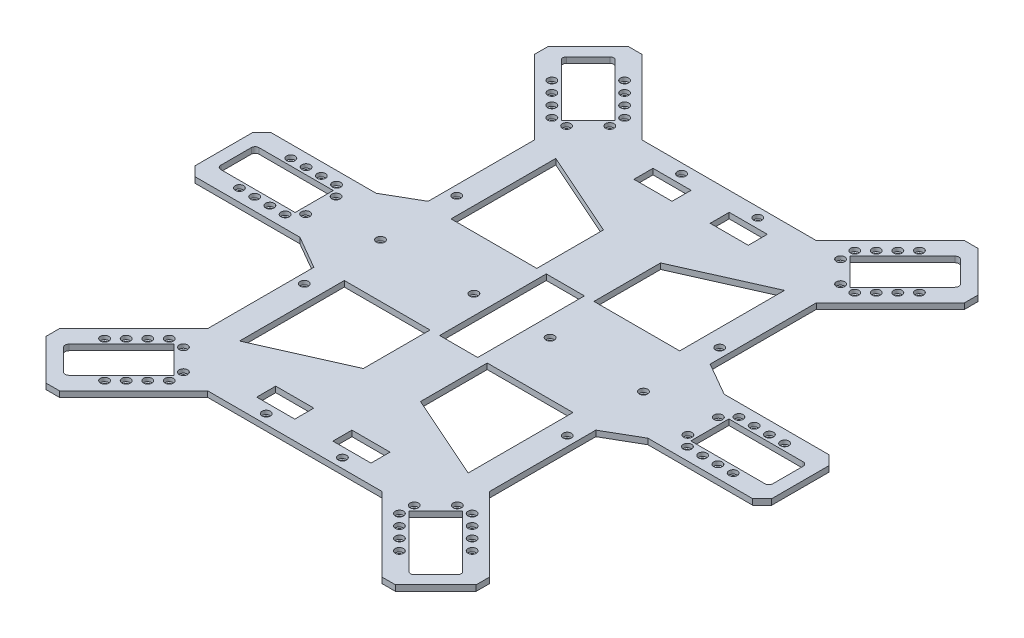
SolidWorks part; units mm, degrees
ref_plane "Front" through (0, 0, 0) normal (0, 0, 1) x (1, 0, 0)
ref_plane "Top" through (0, 0, 0) normal (0, 1, 0) x (1, 0, 0)
ref_plane "Right" through (0, 0, 0) normal (1, 0, 0) x (0, 0, -1)
sketch "草图1" plane through (0, 0, 0) normal (0, 1, 0) x (1, 0, 0)
  line L0 (-45.7157, 114) -> (45.7157, 114)
  line L1 (-74, 0) -> (74, 0) construction
  line L2 (74, -30) -> (91.3205, -20)
  line L3 (91.3205, -20) -> (146.3205, -20)
  line L4 (151.3205, -15) -> (151.3205, 15)
  line L5 (-60, 100) -> (60, -100) construction
  line L6 (-60, -100) -> (60, 100) construction
  line L7 (74, -30) -> (74, -85.7157)
  line L8 (-45.7157, -114) -> (45.7157, -114)
  line L9 (-74, 85.7157) -> (-74, 30)
  line L10 (146.3205, 20) -> (91.3205, 20)
  line L11 (74, 30) -> (91.3205, 20)
  line L12 (0, 100) -> (0, -100) construction
  line L13 (-74, 30) -> (-91.3205, 20)
  line L14 (-146.3205, 20) -> (-91.3205, 20)
  line L15 (-151.3205, -15) -> (-151.3205, 15)
  line L16 (-91.3205, -20) -> (-146.3205, -20)
  line L17 (-74, -30) -> (-91.3205, -20)
  line L18 (-74, -30) -> (-74, -85.7157)
  line L19 (74, 85.7157) -> (74, 30)
  line L20 (91.6777, 152.8909) -> (112.8909, 131.6777)
  line L21 (74, 85.7157) -> (112.8909, 124.6066)
  line L22 (45.7157, 114) -> (84.6066, 152.8909)
  line L23 (-74, 85.7157) -> (-112.8909, 124.6066)
  line L24 (-91.6777, 152.8909) -> (-112.8909, 131.6777)
  line L25 (-45.7157, 114) -> (-84.6066, 152.8909)
  line L26 (74, -85.7157) -> (112.8909, -124.6066)
  line L27 (91.6777, -152.8909) -> (112.8909, -131.6777)
  line L28 (45.7157, -114) -> (84.6066, -152.8909)
  line L29 (-74, -85.7157) -> (-112.8909, -124.6066)
  line L30 (-91.6777, -152.8909) -> (-112.8909, -131.6777)
  line L31 (-45.7157, -114) -> (-84.6066, -152.8909)
  line L32 (-84.6066, 152.8909) -> (-91.6777, 152.8909)
  line L33 (-112.8909, 131.6777) -> (-112.8909, 124.6066)
  line L34 (-151.3205, 15) -> (-146.3205, 20)
  line L35 (-146.3205, -20) -> (-151.3205, -15)
  line L36 (-112.8909, -124.6066) -> (-112.8909, -131.6777)
  line L37 (-84.6066, -152.8909) -> (-91.6777, -152.8909)
  line L38 (84.6066, -152.8909) -> (91.6777, -152.8909)
  line L39 (112.8909, -131.6777) -> (112.8909, -124.6066)
  line L40 (146.3205, -20) -> (151.3205, -15)
  line L41 (151.3205, 15) -> (146.3205, 20)
  line L42 (112.8909, 124.6066) -> (112.8909, 131.6777)
  line L43 (84.6066, 152.8909) -> (91.6777, 152.8909)
  point P0 (0, 0)
  point P12 (74, 30)
  point P16 (74, -30)
extrude "凸台-拉伸1" add sketch "草图1" along normal blind 3
sketch "草图2" plane through (0, 3, 0) normal (0, 1, 0) x (1, 0, 0)
  line L0 (151.3205, 0) -> (87.3942, 0) construction
  line L1 (151.3205, -15) -> (151.3205, 15) construction
  line L2 (103.8205, -10) -> (103.8205, 10)
  line L3 (103.8205, 10) -> (142.8205, 10)
  line L4 (103.8205, -10) -> (142.8205, -10)
  line L7 (144.8205, -15) -> (144.8205, 15)
  line L8 (144.8205, -8) -> (144.8205, 8)
  arc A0 (142.8205, -10) -> (144.8205, -8) centre (142.8205, -8) ccw
  arc A1 (144.8205, 8) -> (142.8205, 10) centre (142.8205, 8) ccw
  point P11 (103.8205, 0)
  dimension "D5" = 6.5
  dimension "D1" = 2
  dimension "D3" = 20
extrude "切除-拉伸1" cut sketch "草图2" against normal up to next
sketch "草图3" plane through (0, 3, 0) normal (0, 1, 0) x (1, 0, 0)
  line L0 (142.8205, 10) -> (103.8205, 10) construction
  line L1 (103.8205, 10) -> (103.8205, -10) construction
  line L2 (151.3205, 0) -> (86.0016, 0) construction
  line L3 (151.3205, -15) -> (151.3205, 15) construction
  point P0 (105.5705, 13.5)
  point P10 (100.3205, 8)
  point P12 (113.5705, 13.5)
  point P13 (121.5705, 13.5)
  point P14 (129.5705, 13.5)
  point P15 (129.5705, -13.5)
  point P16 (121.5705, -13.5)
  point P17 (113.5705, -13.5)
  point P18 (105.5705, -13.5)
  point P19 (100.3205, -8)
  dimension "D1" = 3.5
  dimension "D2" = 1.75
  dimension "D4" = 3.5
  dimension "D5" = 2
  dimension "D3" = 4
hole_wizard "M2 凹头盖螺钉的柱形沉头孔2" positions "3D草图1" profile "草图9" counterbore size "M2" standard "ANSI Metric" end condition through all
sketch3d "3D草图1"
  point P0 (100.3205, 3, -8)
  point P3 (105.5705, 3, -13.5)
  point P6 (113.5705, 3, -13.5)
  point P9 (121.5705, 3, -13.5)
  point P12 (129.5705, 3, -13.5)
  point P15 (100.3205, 3, 8)
  point P18 (105.5705, 3, 13.5)
  point P21 (113.5705, 3, 13.5)
  point P24 (121.5705, 3, 13.5)
  point P27 (129.5705, 3, 13.5)
sketch "草图9" plane through (100.3205, 3, -8) normal (1, 0, 0) x (0, 0, 1)
  line L0 (0, 0) -> (0, 3)
  line L1 (0, 3) -> (1.2, 3)
  line L3 (1.2, 3) -> (1.2, 2)
  line L4 (1.2, 2) -> (2.2, 2)
  line L5 (2.2, 2) -> (2.2, 0)
  line L7 (2.2, 0) -> (0, 0)
  line L11 (0, -6.35) -> (0, 107.95) construction
  dimension "通孔孔直径" = 2.4
  dimension "通孔孔深度" = 3
  dimension "柱形沉头孔直径" = 4.4
  dimension "柱形沉头孔深度" = 2
sketch "草图10" plane through (0, 3, 0) normal (0, 1, 0) x (1, 0, 0)
  line L0 (102.2843, 142.2843) -> (57.3662, 97.3662) construction
  line L1 (112.8909, 131.6777) -> (91.6777, 152.8909) construction
  line L2 (75.7678, 101.6256) -> (61.6256, 115.7678)
  line L3 (61.6256, 115.7678) -> (79.9162, 134.0583)
  line L4 (75.7678, 101.6256) -> (94.0583, 119.9162)
  line L5 (97.6881, 137.6881) -> (103.3449, 132.0312)
  line L6 (94.0583, 119.9162) -> (103.3449, 129.2028)
  line L7 (79.9162, 134.0583) -> (89.2028, 143.3449)
  line L8 (92.0312, 143.3449) -> (97.6881, 137.6881)
  arc A0 (103.3449, 129.2028) -> (103.3449, 132.0312) centre (101.9307, 130.617) ccw
  arc A1 (92.0312, 143.3449) -> (89.2028, 143.3449) centre (90.617, 141.9307) ccw
  point P9 (68.6967, 108.6967)
  dimension "D1" = 6.5
  dimension "D2" = 2
extrude "切除-拉伸2" cut sketch "草图10" against normal up to next
sketch "草图16" plane through (0, 3, 0) normal (0, 1, 0) x (1, 0, 0)
  line L0 (102.2843, 142.2843) -> (58.019, 98.019) construction
  line L1 (112.8909, 131.6777) -> (91.6777, 152.8909) construction
  line L2 (61.6256, 115.7678) -> (75.7678, 101.6256) construction
  line L3 (89.2028, 143.3449) -> (61.6256, 115.7678) construction
  line L4 (60.3882, 119.4801) -> (80.2149, 139.3067) construction
  point P0 (60.3882, 119.4801)
  point P1 (60.565, 111.8787)
  point P12 (66.045, 125.1369)
  point P13 (71.7019, 130.7938)
  point P14 (77.3588, 136.4506)
  point P15 (96.4506, 117.3588)
  point P16 (90.7938, 111.7019)
  point P17 (85.1369, 106.045)
  point P18 (79.4801, 100.3882)
  point P19 (71.8787, 100.565)
  dimension "D1" = 3.5
  dimension "D2" = 2
  dimension "D3" = 1.75
  dimension "D4" = 3.5
  dimension "D5" = 8
  dimension "D6" = 8
  dimension "D7" = 8
hole_wizard "M2 凹头盖螺钉的柱形沉头孔3" positions "3D草图3" profile "草图17" counterbore size "M2" standard "ANSI Metric" end condition through all
sketch3d "3D草图3"
  point P0 (60.3882, 3, -119.4801)
  point P3 (66.045, 3, -125.1369)
  point P6 (71.7019, 3, -130.7938)
  point P9 (77.3588, 3, -136.4506)
  point P12 (60.565, 3, -111.8787)
  point P15 (71.8787, 3, -100.565)
  point P18 (79.4801, 3, -100.3882)
  point P21 (85.1369, 3, -106.045)
  point P24 (90.7938, 3, -111.7019)
  point P27 (96.4506, 3, -117.3588)
sketch "草图17" plane through (60.3882, 3, -119.4801) normal (1, 0, 0) x (0, 0, 1)
  line L0 (0, 0) -> (0, 3)
  line L1 (0, 3) -> (1.2, 3)
  line L3 (1.2, 3) -> (1.2, 2)
  line L4 (1.2, 2) -> (2.2, 2)
  line L5 (2.2, 2) -> (2.2, 0)
  line L7 (2.2, 0) -> (0, 0)
  line L11 (0, -6.35) -> (0, 107.95) construction
  dimension "通孔孔直径" = 2.4
  dimension "通孔孔深度" = 3
  dimension "柱形沉头孔直径" = 4.4
  dimension "柱形沉头孔深度" = 2
mirror "镜向5" about plane through (0, 0, 0) normal (1, 0, 0) of "切除-拉伸1", "M2 凹头盖螺钉的柱形沉头孔2"
mirror "镜向6" about plane through (0, 0, 0) normal (1, 0, 0) of "切除-拉伸2", "M2 凹头盖螺钉的柱形沉头孔3"
mirror "镜向7" about plane through (0, 0, 0) normal (0, 0, 1) of "切除-拉伸2", "M2 凹头盖螺钉的柱形沉头孔3", "镜向6"
sketch "草图18" plane through (0, 3, 0) normal (0, 1, 0) x (1, 0, 0)
  line L0 (0, 114) -> (0, -114) construction
  line L1 (45.7157, 114) -> (-45.7157, 114) construction
  line L2 (-45.7157, -114) -> (45.7157, -114) construction
  line L3 (-151.3205, 0) -> (151.3205, 0) construction
  line L4 (-151.3205, 15) -> (-151.3205, -15) construction
  line L5 (-60, -28) -> (-15, -28)
  line L6 (-15, -28) -> (-15, -63)
  line L7 (-15, -63) -> (-60, -83)
  line L8 (-60, -83) -> (-60, -28)
  line L12 (10, -94) -> (30, -94)
  line L13 (-10, -94) -> (-30, -94)
  line L14 (-10, -94) -> (-10, -104)
  line L15 (-10, -104) -> (-30, -104)
  line L16 (-30, -94) -> (-30, -104)
  line L17 (-10, -94) -> (-30, -104) construction
  line L18 (-10, -104) -> (-30, -94) construction
  line L19 (10, -104) -> (30, -104)
  line L20 (10, -94) -> (10, -104)
  line L21 (30, -94) -> (30, -104)
  line L22 (15, -63) -> (60, -83)
  line L23 (60, -83) -> (60, -28)
  line L25 (15, -28) -> (15, -63)
  line L26 (60, -28) -> (15, -28)
  line L27 (-10, 104) -> (-30, 104)
  line L28 (-30, 94) -> (-30, 104)
  line L29 (-10, 94) -> (-30, 94)
  line L30 (-10, 94) -> (-10, 104)
  line L31 (30, 94) -> (30, 104)
  line L32 (10, 104) -> (30, 104)
  line L33 (10, 94) -> (10, 104)
  line L34 (10, 94) -> (30, 94)
  line L35 (15, 63) -> (60, 83)
  line L36 (60, 83) -> (60, 28)
  line L37 (60, 28) -> (15, 28)
  line L38 (15, 28) -> (15, 63)
  line L39 (-15, 28) -> (-15, 63)
  line L40 (-60, 28) -> (-15, 28)
  line L41 (-60, 83) -> (-60, 28)
  line L42 (-15, 63) -> (-60, 83)
  point P17 (-20, -99)
  point P32 (0, -20)
  point P33 (0, -10)
  dimension "D5" = 60
  dimension "D6" = 45
  dimension "D7" = 55
  dimension "D8" = 35
  dimension "D9" = 20
  dimension "D10" = 10
  dimension "D11" = 10
  dimension "D12" = 10
extrude "切除-拉伸3" cut sketch "草图18" against normal up to next
sketch "草图19" plane through (0, 3, 0) normal (0, 1, 0) x (1, 0, 0)
  line L0 (0, 114) -> (0, -114) construction
  line L1 (45.7157, 114) -> (-45.7157, 114) construction
  line L2 (-45.7157, -114) -> (45.7157, -114) construction
  line L3 (-151.3205, 0) -> (151.3205, 0) construction
  line L4 (-151.3205, 15) -> (-151.3205, -15) construction
  line L5 (-10, 94) -> (-10, 104) construction
  point P0 (-20, 109)
  point P14 (20, 109)
  point P15 (20, -109)
  point P16 (-20, -109)
  point P17 (-20, 0)
  point P18 (20, 0)
  dimension "D1" = 5
  dimension "D2" = 10
hole_wizard "M2 凹头盖螺钉的柱形沉头孔4" positions "3D草图4" profile "草图20" counterbore size "M2" standard "ANSI Metric" end condition through all
sketch3d "3D草图4"
  point P0 (-20, 3, 109)
  point P3 (20, 3, 109)
  point P6 (-20, 3, -109)
  point P9 (20, 3, -109)
sketch "草图20" plane through (-20, 3, 109) normal (1, 0, 0) x (0, 0, 1)
  line L0 (0, 0) -> (0, 3)
  line L1 (0, 3) -> (1.2, 3)
  line L3 (1.2, 3) -> (1.2, 2)
  line L4 (1.2, 2) -> (2.2, 2)
  line L5 (2.2, 2) -> (2.2, 0)
  line L7 (2.2, 0) -> (0, 0)
  line L11 (0, -6.35) -> (0, 107.95) construction
  dimension "通孔孔直径" = 2.4
  dimension "通孔孔深度" = 3
  dimension "柱形沉头孔直径" = 4.4
  dimension "柱形沉头孔深度" = 2
sketch "草图21" plane through (0, 3, 0) normal (0, 1, 0) x (1, 0, 0)
  line L0 (-74, 85.7157) -> (-74, 30) construction
  line L1 (74, 30) -> (74, 85.7157) construction
  line L2 (-60, 28) -> (-15, 28) construction
  line L3 (15, 28) -> (60, 28) construction
  point P0 (-69, 40)
  point P1 (69, 40)
  point P6 (-69, 0)
  point P11 (69, 0)
  dimension "D1" = 5
  dimension "D2" = 5
  dimension "D3" = 12
  dimension "D4" = 12
  dimension "D5" = 40
hole_wizard "M2 凹头盖螺钉的柱形沉头孔5" positions "3D草图5" profile "草图22" counterbore size "M2" standard "ANSI Metric" end condition through all
sketch3d "3D草图5"
  point P0 (-69, 3, -40)
  point P3 (69, 3, -40)
sketch "草图22" plane through (-69, 3, -40) normal (1, 0, 0) x (0, 0, 1)
  line L0 (0, 0) -> (0, 3)
  line L1 (0, 3) -> (1.2, 3)
  line L3 (1.2, 3) -> (1.2, 2)
  line L4 (1.2, 2) -> (2.2, 2)
  line L5 (2.2, 2) -> (2.2, 0)
  line L7 (2.2, 0) -> (0, 0)
  line L11 (0, -6.35) -> (0, 107.95) construction
  dimension "通孔孔直径" = 2.4
  dimension "通孔孔深度" = 3
  dimension "柱形沉头孔直径" = 4.4
  dimension "柱形沉头孔深度" = 2
mirror "镜向8" about plane through (0, 0, 0) normal (0, 0, 1) of "M2 凹头盖螺钉的柱形沉头孔5"
hole_wizard "M2 凹头盖螺钉的柱形沉头孔6" positions "3D草图6" profile "草图23" counterbore size "M2" standard "ANSI Metric" end condition through all
sketch3d "3D草图6"
  point P0 (-69, 3, 0)
  point P3 (69, 3, 0)
sketch "草图23" plane through (-69, 3, 0) normal (1, 0, 0) x (0, 0, 1)
  line L0 (0, 0) -> (0, 3)
  line L1 (0, 3) -> (1.2, 3)
  line L3 (1.2, 3) -> (1.2, 2)
  line L4 (1.2, 2) -> (2.2, 2)
  line L5 (2.2, 2) -> (2.2, 0)
  line L7 (2.2, 0) -> (0, 0)
  line L11 (0, -6.35) -> (0, 107.95) construction
  dimension "通孔孔直径" = 2.4
  dimension "通孔孔深度" = 3
  dimension "柱形沉头孔直径" = 4.4
  dimension "柱形沉头孔深度" = 2
sketch "草图24" plane through (0, 3, 0) normal (0, 1, 0) x (1, 0, 0)
  line L3 (-10, 28) -> (10, 28)
  line L4 (-10, 28) -> (-10, -28)
  line L5 (-10, -28) -> (10, -28)
  line L6 (10, 28) -> (10, -28)
  line L7 (-10, 28) -> (10, -28) construction
  line L8 (-10, -28) -> (10, 28) construction
  point P0 (0, 0)
  dimension "D1" = 20
  dimension "D2" = 56
extrude "切除-拉伸4" cut sketch "草图24" against normal blind 10
hole_wizard "M2 凹头盖螺钉的柱形沉头孔7" positions "3D草图7" profile "草图25" counterbore size "M2" standard "ANSI Metric" end condition through all
sketch3d "3D草图7"
  point P0 (-20, 3, 0)
  point P3 (20, 3, 0)
sketch "草图25" plane through (-20, 3, 0) normal (1, 0, 0) x (0, 0, 1)
  line L0 (0, 0) -> (0, 3)
  line L1 (0, 3) -> (1.2, 3)
  line L3 (1.2, 3) -> (1.2, 2)
  line L4 (1.2, 2) -> (2.2, 2)
  line L5 (2.2, 2) -> (2.2, 0)
  line L7 (2.2, 0) -> (0, 0)
  line L11 (0, -6.35) -> (0, 107.95) construction
  dimension "通孔孔直径" = 2.4
  dimension "通孔孔深度" = 3
  dimension "柱形沉头孔直径" = 4.4
  dimension "柱形沉头孔深度" = 2
